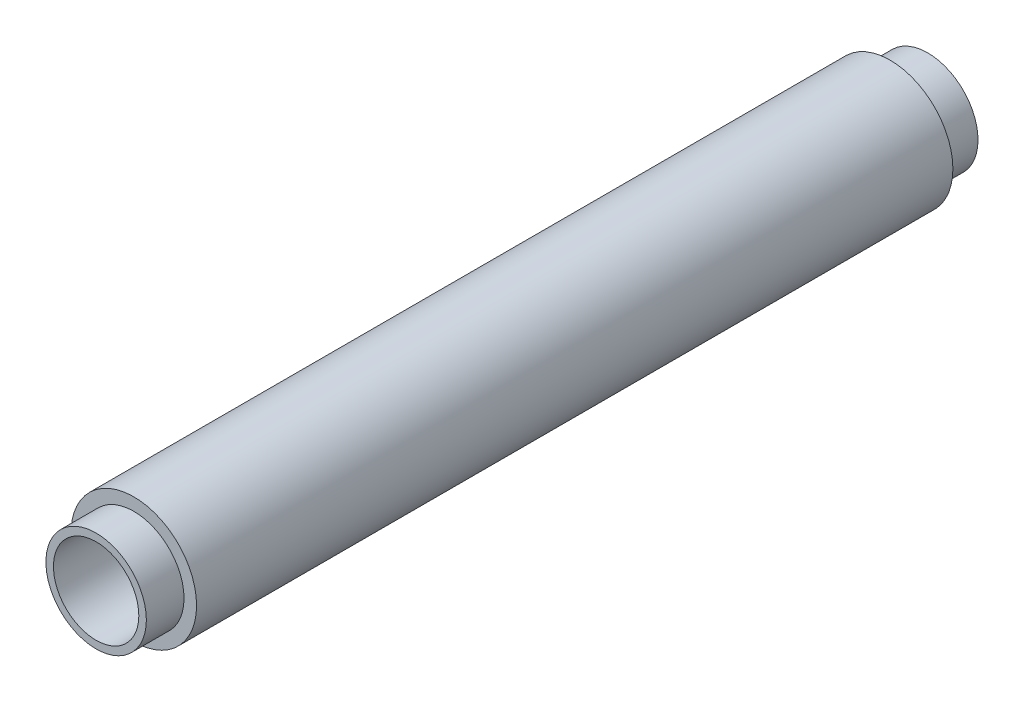
SolidWorks part; units mm, degrees
material "СТ3КП"
ref_plane "Спереди" through (0, 0, 0) normal (0, 0, 1) x (1, 0, 0)
ref_plane "Сверху" through (0, 0, 0) normal (0, 1, 0) x (1, 0, 0)
ref_plane "Справа" through (0, 0, 0) normal (1, 0, 0) x (0, 0, -1)
sketch "Эскиз1" plane through (0, 0, 0) normal (0, 1, 0) x (1, 0, 0)
  line L0 (-1000, 0) -> (49000, 0) construction
  line L1 (0, -1000) -> (0, 49000) construction
  line L3 (-25, 0) -> (-17, 0)
  line L4 (-25, 0) -> (-25, -150.6)
  line L5 (-20, -165.6) -> (-17, -165.6)
  line L6 (-17, 0) -> (-17, -165.6)
  line L7 (-21.5, -165.6) -> (21.5, -165.6) construction
  line L8 (21.5, -150.6) -> (-21.5, -150.6) construction
  line L9 (-20, -150.6) -> (-25, -150.6)
  line L10 (-20, -150.6) -> (-20, -165.6)
  line L13 (-20, -152.1) -> (-20, -164.1) construction
  dimension "D1" = 34
  dimension "D2" = 50
revolve "Повернуть1" add sketch "Эскиз1" angle 360 about L1
mirror "Зеркальное отражение1" about plane through (-25, 0, 0) normal (0, 0, 1) of "Повернуть1"
